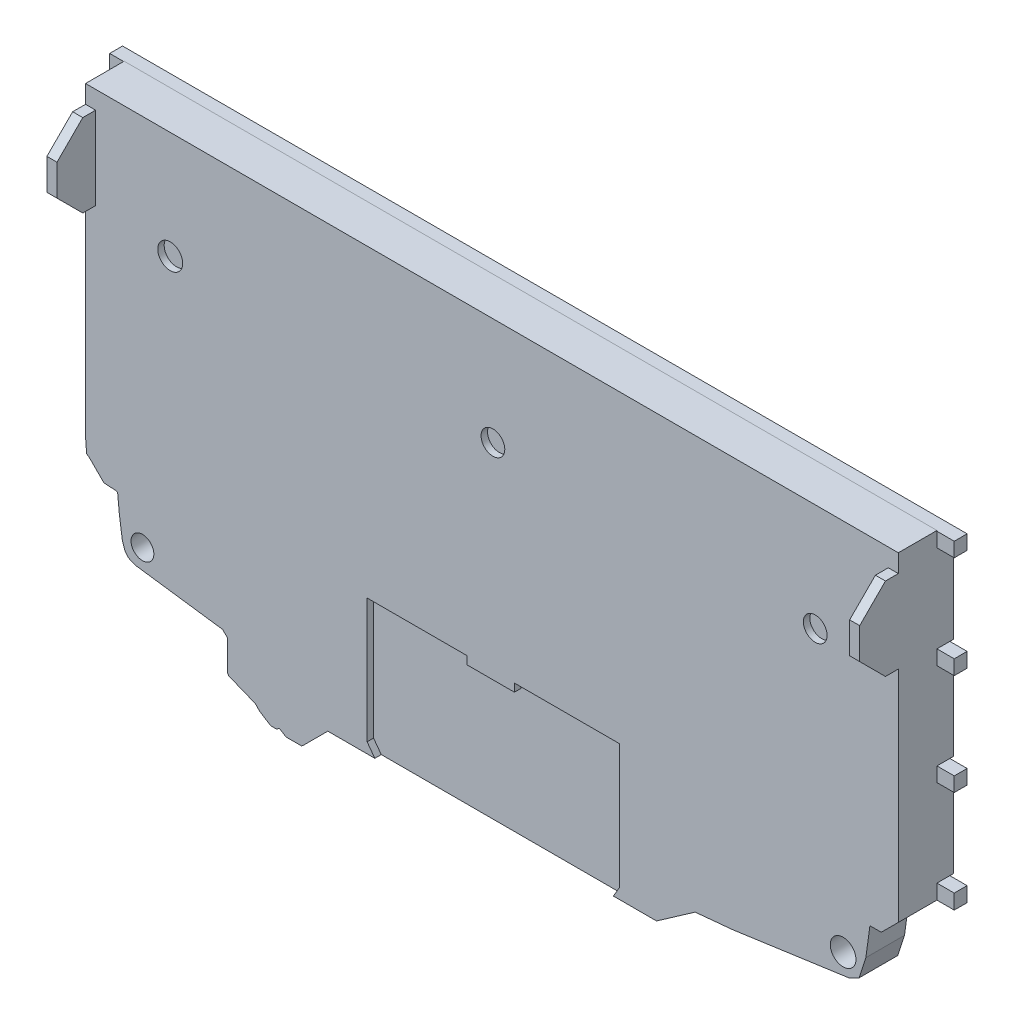
SolidWorks part; units mm, degrees
ref_plane "Plan de face" through (0, 0, 0) normal (0, 0, 1) x (1, 0, 0)
ref_plane "Plan de dessus" through (0, 0, 0) normal (0, 1, 0) x (1, 0, 0)
ref_plane "Plan de droite" through (0, 0, 0) normal (1, 0, 0) x (0, 0, -1)
sketch "Contours" plane through (0, 0, 0) normal (0, 0, 1) x (1, 0, 0)
  line L0 (-13.1473, 8.2424) -> (49.3527, 8.2424) construction
  line L5 (-13.5371, 8.689) -> (49.4272, 8.689)
  line L6 (49.4272, 8.689) -> (49.4272, -15.576)
  line L7 (49.4272, -15.576) -> (49.4272, -16.167)
  line L8 (49.4272, -16.167) -> (48.103, -17.4912)
  line L9 (48.103, -17.4912) -> (47.2221, -17.4912)
  line L10 (47.2221, -17.4912) -> (46.9055, -19.7973)
  line L11 (46.9055, -19.7973) -> (46.3778, -21.4225)
  line L12 (46.3778, -21.4225) -> (45.6118, -21.813)
  line L13 (45.6118, -21.813) -> (43.444, -22.119)
  line L14 (43.444, -22.119) -> (40.6272, -22.5166)
  line L15 (40.6272, -22.5166) -> (36.6077, -23.084)
  line L16 (36.6077, -23.084) -> (33.6507, -23.3643)
  line L17 (33.6507, -23.3643) -> (30.6545, -25.4572)
  line L18 (30.6545, -25.4572) -> (5.1292, -25.4572)
  line L19 (5.1292, -25.4572) -> (3.2101, -27.3764)
  line L20 (3.2101, -27.3764) -> (3.0865, -27.4692)
  line L21 (3.0865, -27.4692) -> (1.8825, -27.4692)
  line L22 (1.8825, -27.4692) -> (1.3684, -27.1445)
  line L23 (1.3684, -27.1445) -> (1.1522, -27.3069)
  line L24 (1.1522, -27.3069) -> (0.692, -27.3069)
  line L25 (0.692, -27.3069) -> (-0.1677, -26.7639)
  line L26 (-0.4985, -26.4168) -> (-0.1677, -26.7639)
  line L27 (-0.4985, -26.4168) -> (-2.5548, -25.5888)
  line L28 (-2.5548, -25.5888) -> (-2.6536, -25.4572)
  line L29 (-2.6536, -25.4572) -> (-2.6536, -23.084)
  line L30 (-2.6536, -23.084) -> (-3.036, -22.7016)
  line L31 (-3.036, -22.7016) -> (-9.781, -21.7756)
  line L32 (-9.781, -21.7756) -> (-10.3585, -21.543)
  line L33 (-10.3585, -21.543) -> (-10.6396, -21.1687)
  line L34 (-10.6396, -21.1687) -> (-10.8239, -20.6099)
  line L35 (-10.8239, -20.6099) -> (-10.9165, -19.954)
  line L36 (-10.9165, -19.954) -> (-11.0603, -18.9352)
  line L37 (-11.0603, -18.9352) -> (-11.1842, -17.6281)
  line L38 (-11.3249, -17.5117) -> (-12.2612, -17.4421)
  line L39 (-12.2612, -17.4421) -> (-12.7463, -16.957)
  line L40 (-12.7463, -16.957) -> (-13.412, -16.2913)
  line L41 (-13.412, -16.2913) -> (-13.5998, -16.167)
  line L42 (-13.5998, -16.167) -> (-13.6831, -15.0234)
  line L43 (-13.6831, -15.0234) -> (-13.6831, 8.689)
  line L44 (-13.6831, 8.689) -> (-13.5371, 8.689)
  arc A0 (-11.1842, -17.6281) -> (-11.3249, -17.5117) centre (-11.3128, -17.6403) ccw
  circle A1 centre (45.1403, -20.301) radius 0.9968
  circle A2 centre (-9.2638, -20.301) radius 0.8845
  circle A3 centre (-7.1071, 0.3611) radius 0.9695
  circle A4 centre (17.9506, 0.3611) radius 0.9202
  circle A5 centre (42.9755, 0.3611) radius 0.9202
  point P0 (8.2624, -15.0234)
  point P1 (15.9754, -15.0234)
  point P2 (15.9754, -15.576)
  point P3 (19.6858, -15.576)
  point P48 (19.9981, -15.0234)
  point P49 (27.7542, -15.0234)
  point P50 (27.7542, -24.6563)
  point P51 (27.3378, -25.4572)
  point P52 (8.8064, -25.4572)
  point P53 (8.2624, -24.6563)
  point P54 (-14.7921, 8.635)
  point P55 (-13.6967, 8.635)
  point P56 (-14.7921, 7.5162)
  point P57 (-13.7158, 7.5162)
  point P58 (50.7766, 8.635)
  point P59 (50.7766, 7.5162)
  point P60 (49.5383, 7.5162)
  point P61 (49.5383, 8.635)
  point P62 (50.7766, 0.7101)
  point P63 (50.7766, -0.3697)
  point P64 (49.5383, -0.3697)
  point P65 (49.5383, 0.7101)
  point P66 (50.7766, -7.1609)
  point P67 (50.7766, -8.2746)
  point P68 (49.6467, -8.2746)
  point P69 (49.6467, -7.1609)
  point P70 (50.7766, -15.0234)
  point P71 (50.7766, -16.167)
  point P72 (49.6467, -16.167)
  point P73 (49.6467, -15.0234)
  point P74 (-14.9338, -15.0234)
  point P75 (-13.8373, -15.0234)
  point P76 (-14.9338, -16.167)
  point P77 (-13.8373, -16.167)
  point P78 (-14.9338, -7.1609)
  point P79 (-13.8373, -7.1609)
  point P80 (-14.9338, -8.2746)
  point P81 (-13.8373, -8.2746)
  point P82 (-14.7921, 0.7101)
  point P83 (-13.8373, 0.7101)
  point P84 (-13.8373, -0.3697)
  point P85 (-14.7921, -0.3697)
  dimension "D1" = 62.5
extrude "Boss.-Extru.1" add sketch "Contours" along normal blind 3
sketch "Esquisse4" plane through (0, 0, 0) normal (0, 0, 1) x (1, 0, 0)
  line L0 (5.1292, -25.4572) -> (30.6545, -25.4572) construction
  line L1 (8.1818, -14.9742) -> (15.9379, -14.9742)
  line L2 (15.9379, -14.9742) -> (15.9379, -15.592)
  line L3 (15.9379, -15.592) -> (19.6198, -15.592)
  line L4 (19.6198, -15.592) -> (19.6198, -14.9742)
  line L5 (19.6198, -14.9742) -> (27.7724, -14.9742)
  line L6 (27.7724, -14.9742) -> (27.7724, -24.6477)
  line L7 (27.7724, -24.6477) -> (27.3086, -25.4572)
  line L8 (27.3086, -25.4572) -> (8.7823, -25.4572)
  line L9 (8.7823, -25.4572) -> (8.1818, -24.6477)
  line L10 (8.1818, -24.6477) -> (8.1818, -14.9742)
  point P0 (8.1818, -14.9742)
  point P1 (15.9379, -14.9742)
  point P2 (15.9379, -15.592)
  point P3 (19.6198, -15.592)
  point P4 (19.9615, -14.9742)
  point P5 (27.7724, -14.9742)
  point P6 (27.7724, -24.6477)
  point P7 (27.3086, -25.4572)
  point P8 (8.7823, -25.4572)
  point P11 (8.1818, -24.6477)
sketch "Esquisse5" plane through (0, 0, 3) normal (0, 0, 1) x (1, 0, 0)
  line L0 (8.1818, -14.9742) -> (15.9379, -14.9742)
  line L1 (15.9379, -14.9742) -> (15.9379, -15.592)
  line L2 (15.9379, -15.592) -> (19.6198, -15.592)
  line L3 (19.6198, -15.592) -> (19.6198, -14.9742)
  line L4 (19.6198, -14.9742) -> (27.7724, -14.9742)
  line L5 (27.7724, -14.9742) -> (27.7724, -24.6477)
  line L6 (27.7724, -24.6477) -> (27.3086, -25.4572)
  line L7 (27.3086, -25.4572) -> (8.7823, -25.4572)
  line L8 (8.7823, -25.4572) -> (8.1818, -24.6477)
  line L9 (8.1818, -24.6477) -> (8.1818, -14.9742)
extrude "Enlèv. mat.-Extru.3" cut sketch "Esquisse5" against normal blind 0.5
sketch "Esquisse6" plane through (0, 0, 0) normal (0, 0, 1) x (1, 0, 0)
  circle A0 centre (42.9755, 0.3611) radius 0.9202
  circle A1 centre (17.9506, 0.3611) radius 0.9202
  circle A2 centre (-7.1071, 0.3611) radius 0.9695
extrude "Boss.-Extru.2" add sketch "Esquisse6" along normal blind 2.5
sketch "Esquisse7" plane through (0, 0, 0) normal (0, 0, 1) x (1, 0, 0)
  line L0 (-14.8097, 8.6466) -> (50.768, 8.6352)
  line L1 (50.768, 8.6352) -> (50.768, 7.5179)
  line L2 (50.768, 7.5179) -> (-14.8097, 7.5179)
  line L3 (-14.8097, 7.5179) -> (-14.8097, 8.6466)
  line L4 (-14.8097, 0.729) -> (-14.8097, -0.4066)
  line L5 (-14.8097, -0.4066) -> (50.768, -0.4066)
  line L6 (50.768, -0.4066) -> (50.768, 0.729)
  line L7 (50.768, 0.729) -> (-14.8097, 0.729)
  line L8 (-14.9461, -7.1443) -> (50.768, -7.1443)
  line L9 (50.768, -7.1443) -> (50.768, -8.2659)
  line L10 (50.768, -8.2659) -> (-14.9461, -8.2659)
  line L11 (-14.9461, -8.2659) -> (-14.9461, -7.1443)
  line L12 (-14.9461, -15.0232) -> (50.768, -15.0232)
  line L13 (50.768, -15.0232) -> (50.768, -16.1706)
  line L14 (50.768, -16.1706) -> (-14.9461, -16.1706)
  line L15 (-14.9461, -16.1706) -> (-14.9461, -15.0232)
  point P0 (-14.8097, 8.6466)
  point P1 (50.768, 8.6352)
  point P2 (50.768, 7.5179)
  point P3 (-14.8097, 7.5179)
  point P4 (-14.8097, 0.729)
  point P5 (-14.8097, -0.4066)
  point P6 (-14.8097, -7.1443)
  point P7 (-14.9461, -8.2659)
  point P8 (-14.9461, -7.1443)
  point P9 (-14.9461, -15.0232)
  point P10 (-14.9461, -16.1706)
  point P11 (50.768, 0.729)
  point P12 (50.768, -0.4066)
  point P13 (50.768, -7.1443)
  point P14 (50.768, -8.2659)
  point P15 (50.768, -15.0232)
  point P16 (50.768, -16.1706)
extrude "Boss.-Extru.3" add sketch "Esquisse7" against normal blind 1
sketch "Esquisse8" plane through (0, 0, 0) normal (0, 0, -1) x (-1, 0, 0)
  line L0 (13.6831, 7.5179) -> (-49.4272, 7.5179) construction
  line L1 (-49.4272, 7.5179) -> (13.6831, 7.5179)
  line L2 (-49.4272, 7.5179) -> (-49.4272, 0.729)
  line L3 (-49.4272, 0.729) -> (13.6831, 0.729)
  line L4 (13.6831, 7.5179) -> (13.6831, 0.729)
  line L5 (-49.4272, 0.729) -> (-49.4272, 7.5179) construction
  line L6 (-50.768, -7.1443) -> (14.9461, -7.1443) construction
  line L7 (-49.4272, -0.4066) -> (13.6831, -0.4066)
  line L8 (-49.4272, -0.4066) -> (-49.4272, -7.1443)
  line L9 (-49.4272, -7.1443) -> (13.6831, -7.1443)
  line L10 (13.6831, -0.4066) -> (13.6831, -7.1443)
  line L11 (-49.4272, -7.1443) -> (13.6831, -7.1443) construction
  line L12 (13.6831, -8.2659) -> (13.6831, -15.0232) construction
  line L13 (-49.4272, -8.2659) -> (13.6831, -8.2659)
  line L14 (-49.4272, -8.2659) -> (-49.4272, -15.0232)
  line L15 (-49.4272, -15.0232) -> (13.6831, -15.0232)
  line L16 (13.6831, -8.2659) -> (13.6831, -15.0232)
  line L17 (-39.9476, -16.1706) -> (3.4676, -16.1706)
  line L18 (13.5943, -16.1706) -> (-49.4236, -16.1706) construction
  line L19 (2.9289, -19.9041) -> (6.6624, -16.1706)
  line L20 (-4.1421, -22.833) -> (-28.7122, -22.833)
  line L21 (-35.4055, -20.2626) -> (-39.9476, -16.1706)
  line L22 (6.6624, -16.1706) -> (3.4676, -16.1706)
  arc A0 (-4.1421, -22.833) -> (2.9289, -19.9041) centre (-4.1421, -12.833) ccw
  arc A1 (-28.7122, -22.833) -> (-35.4055, -20.2626) centre (-28.7122, -12.833) cw
  dimension "D2" = 10
  dimension "D1" = 6.7573
extrude "Boss.-Extru.4" add sketch "Esquisse8" along normal blind 1.3
sketch "Esquisse12" plane through (0, 0, 3) normal (0, 0, 1) x (1, 0, 0)
  line L0 (49.4272, 8.689) -> (49.4272, 7.289) construction
  line L1 (49.4272, -16.167) -> (49.4272, 8.689) construction
  line L2 (49.4272, 7.289) -> (-13.6831, 7.289) construction
  line L3 (49.4272, 7.289) -> (48.6476, 7.289)
  line L4 (49.4272, 7.289) -> (49.4272, 0.8703)
  line L5 (49.4272, 0.8703) -> (48.6476, 0.8703)
  line L6 (48.6476, 7.289) -> (48.6476, 0.8703)
  line L7 (-13.6831, 8.689) -> (-13.6831, -15.0234) construction
  line L8 (49.4272, 0.8703) -> (-13.6831, 0.8703) construction
  line L10 (-13.6831, 7.289) -> (-12.8976, 7.289)
  line L11 (-13.6831, 7.289) -> (-13.6831, 0.8703)
  line L12 (-13.6831, 0.8703) -> (-12.8976, 0.8703)
  line L13 (-12.8976, 7.289) -> (-12.8976, 0.8703)
extrude "Boss.-Extru.6" add sketch "Esquisse12" along normal blind 3
chamfer "Chanfrein1" distance 2 angle 45 2 edges at (49.0374, 0.8703, 6) (49.0374, 7.289, 6)
chamfer "Chanfrein2" distance 2 angle 45 2 edges at (-13.2904, 0.8703, 6) (-13.2904, 7.289, 6)
